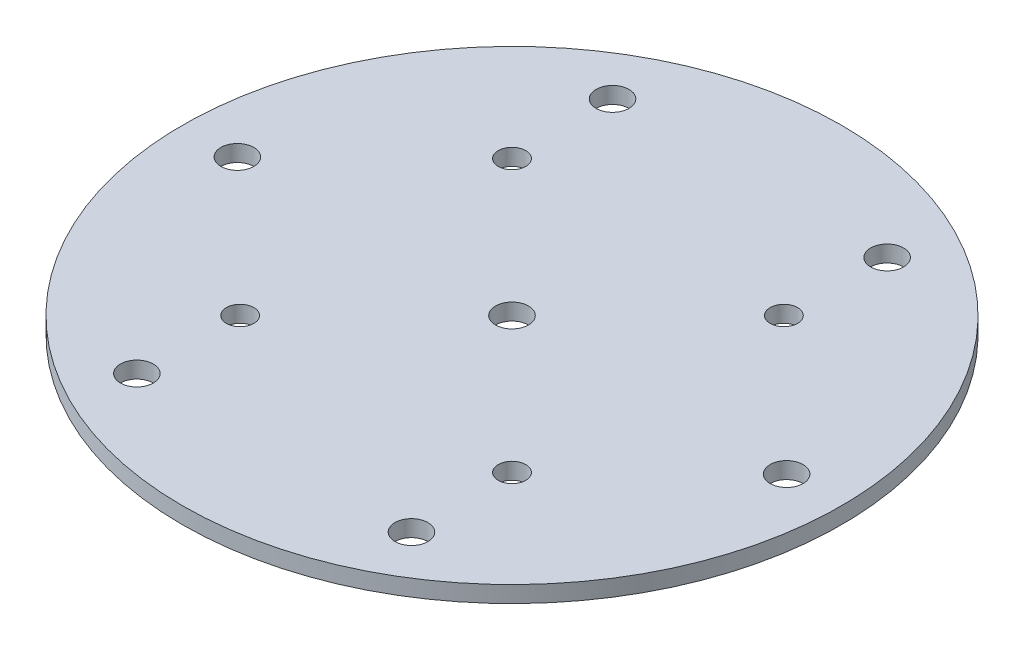
SolidWorks part; units mm, degrees
material "Oak"
ref_plane "Front Plane" through (0, 0, 0) normal (0, 0, 1) x (1, 0, 0)
ref_plane "Top Plane" through (0, 0, 0) normal (0, 1, 0) x (1, 0, 0)
ref_plane "Right Plane" through (0, 0, 0) normal (1, 0, 0) x (0, 0, -1)
sketch "Sketch1" plane through (0, 0, 0) normal (0, 1, 0) x (1, 0, 0)
  line L0 (-60, 0) -> (60, 0) construction
  line L1 (0, -60) -> (0, 60) construction
  line L2 (-42.4264, -42.4264) -> (42.4264, 42.4264) construction
  line L3 (-43.2832, 43.2832) -> (43.2832, -43.2832) construction
  circle A0 centre (0, 0) radius 60
  circle A15 centre (0, 0) radius 50 construction
  circle A16 centre (0, 0) radius 45 construction
  circle A17 centre (-50, 0) radius 3
  circle A22 centre (-25, 43.3013) radius 3
  circle A23 centre (25, 43.3013) radius 3
  circle A24 centre (50, 0) radius 3
  circle A25 centre (25, -43.3013) radius 3
  circle A26 centre (-25, -43.3013) radius 3
  circle A27 centre (-24.7487, 24.7487) radius 2.5
  circle A28 centre (24.7487, 24.7487) radius 2.5
  circle A29 centre (24.7487, -24.7487) radius 2.5
  circle A30 centre (-24.7487, -24.7487) radius 2.5
  point P7 (0, 0)
  point P10 (0, 0)
  point P13 (0, 0)
  point P17 (0, 0)
  point P32 (0, 0)
  point P49 (0, 0)
  dimension "D1" = 120
  dimension "D2" = 100
  dimension "D4" = 35
  dimension "D6" = 6
  dimension "D3" = 45
  dimension "D5" = 4
extrude "Boss-Extrude1" add sketch "Sketch1" along normal blind 3 contours A0 A30 A29 A28 A27 A26 A25 A24 A23 A22 A17
sketch "Sketch2" plane through (0, 3, 0) normal (0, 1, 0) x (1, 0, 0)
  circle A0 centre (0, 0) radius 3
extrude "Cut-Extrude1" cut sketch "Sketch2" against normal through all both
